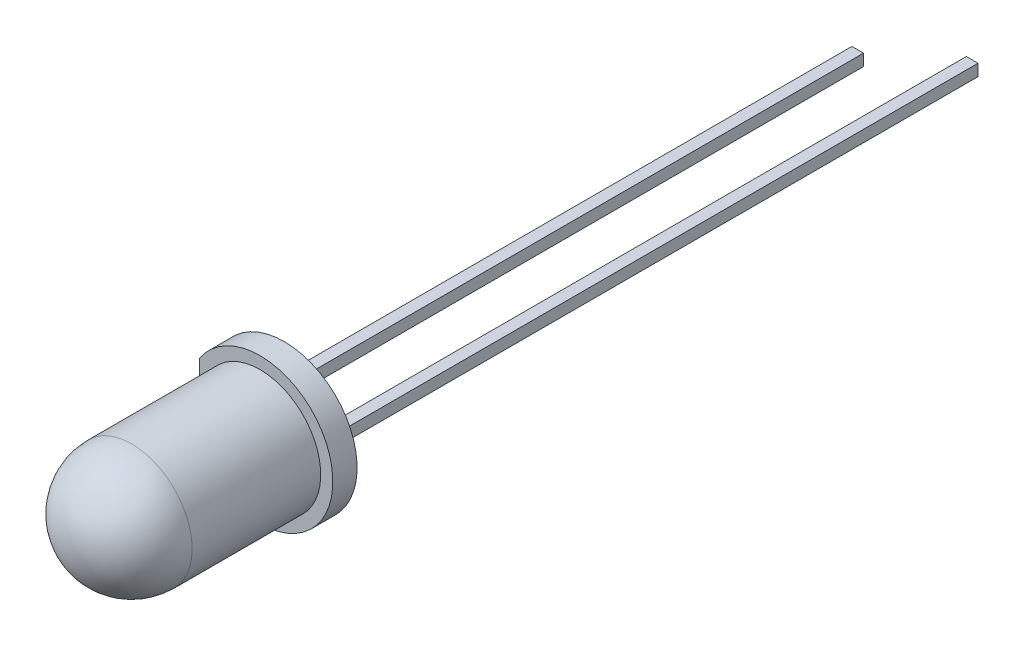
SolidWorks part; units mm, degrees
ref_plane "Plano frontal" through (0, 0, 0) normal (0, 0, 1) x (1, 0, 0)
ref_plane "Plano superior" through (0, 0, 0) normal (0, 1, 0) x (1, 0, 0)
ref_plane "Plano direito" through (0, 0, 0) normal (1, 0, 0) x (0, 0, -1)
sketch "Esboço1" plane through (0, 0, 0) normal (0, 0, 1) x (1, 0, 0)
  circle A0 centre (0, 0) radius 3
extrude "Ressalto-extrusão1" add sketch "Esboço1" along normal blind 1
sketch "Esboço3" plane through (0, 0, 0) normal (1, 0, 0) x (0, 0, -1)
  line L0 (-1, 0) -> (-8.8, 0)
  line L1 (-1, 3) -> (-1, -3) construction
  line L2 (-6.3, 2.5) -> (-1, 2.5)
  line L3 (-1, 0) -> (-1, 2.5)
  arc A0 (-8.8, 0) -> (-6.3, 2.5) centre (-6.3, 0) cw
revolve "Revolução1" add sketch "Esboço3" angle 360 about L0
sketch "Esboço4" plane through (0, 0, 0) normal (0, 0, -1) x (-1, 0, 0)
  line L0 (2.5, 1.6583) -> (2.5, -1.6583)
  circle A0 centre (0, 0) radius 3 construction
  arc A1 (2.5, -1.6583) -> (2.5, 1.6583) centre (0, 0) ccw
  circle A2 centre (0, 0) radius 2.5 construction
extrude "Corte-extrusão1" cut sketch "Esboço4" against normal up to surface (1 mm away) up to face at (2.5, 0, 1)
sketch "Esboço5" plane through (0, 0, 0) normal (0, 0, -1) x (-1, 0, 0)
  line L0 (-1.12, 0) -> (1.12, 0) construction
  line L1 (-1.6, -0.24) -> (-1.12, -0.24)
  line L2 (-1.6, -0.24) -> (-1.6, 0.24)
  line L3 (-1.6, 0.24) -> (-1.12, 0.24)
  line L4 (-1.12, -0.24) -> (-1.12, 0.24)
  line L5 (1.12, -0.24) -> (1.6, -0.24)
  line L6 (1.12, -0.24) -> (1.12, 0.24)
  line L7 (1.12, 0.24) -> (1.6, 0.24)
  line L8 (1.6, -0.24) -> (1.6, 0.24)
extrude "Ressalto-extrusão2" add sketch "Esboço5" along normal blind 25 separate body
sketch "Esboço6" plane through (0, 0, -25) normal (0, 0, -1) x (-1, 0, 0)
  line L4 (-1.6, 0.24) -> (-1.6, -0.24)
  line L5 (-1.6, -0.24) -> (-1.12, -0.24)
  line L6 (-1.12, -0.24) -> (-1.12, 0.24)
  line L7 (-1.12, 0.24) -> (-1.6, 0.24)
  line L8 (-1.6, 0.24) -> (-1.6, -0.24)
  line L9 (-1.6, -0.24) -> (-1.12, -0.24)
  line L10 (-1.12, -0.24) -> (-1.12, 0.24)
  line L11 (-1.12, 0.24) -> (-1.6, 0.24)
extrude "Ressalto-extrusão3" add sketch "Esboço6" along normal blind 2 separate body
sketch "Esboço7" plane through (0, 0, 0) normal (0, 1, 0) x (1, 0, 0)
  line L0 (-1.6, 0) -> (-1.6, -3.5)
  line L1 (-1.12, 0) -> (-1.12, -2)
  line L2 (0.02, -2) -> (1.2, -4)
  line L3 (1.2, -4) -> (-1.3, -4)
  line L4 (-1.3, -4) -> (-1.6, -3.5)
  line L5 (-1.12, -2) -> (0.02, -2)
  line L6 (1.6, 0) -> (1.6, -4)
  line L7 (1.6, -4) -> (1.4, -4)
  line L8 (1.4, -4) -> (0.22, -2)
  line L9 (0.22, -2) -> (1.12, -2)
  line L10 (1.12, -2) -> (1.12, 0)
  line L11 (-1.6, 0) -> (-1.12, 0)
  line L12 (1.12, 0) -> (1.6, 0)
extrude "Corte-extrusão2" cut sketch "Esboço7" against normal mid plane 0.48
sketch "Esboço8" plane through (0, 0, 0) normal (0, 1, 0) x (1, 0, 0)
  line L0 (-1.3, -4) -> (1.2, -4) construction
  line L1 (-1.6, -3.5) -> (-1.3, -4) construction
  line L2 (-1.6, 0) -> (-1.6, -3.5) construction
  line L3 (1.2, -4) -> (0.02, -2) construction
  line L4 (0.02, -2) -> (-1.12, -2) construction
  line L5 (-1.12, -2) -> (-1.12, 0) construction
  line L6 (0.22, -2) -> (1.4, -4) construction
  line L7 (1.12, -2) -> (0.22, -2) construction
  line L8 (1.12, 0) -> (1.12, -2) construction
  line L9 (1.6, -4) -> (1.6, 0) construction
  line L10 (1.4, -4) -> (1.6, -4) construction
  line L11 (-1.12, 0) -> (-1.6, 0) construction
  line L12 (1.6, 0) -> (1.12, 0) construction
  line L13 (-1.3, -4) -> (1.2, -4)
  line L14 (-1.6, -3.5) -> (-1.3, -4)
  line L15 (-1.6, 0) -> (-1.6, -3.5)
  line L16 (1.2, -4) -> (0.02, -2)
  line L17 (0.02, -2) -> (-1.12, -2)
  line L18 (-1.12, -2) -> (-1.12, 0)
  line L19 (0.22, -2) -> (1.4, -4)
  line L20 (1.12, -2) -> (0.22, -2)
  line L21 (1.12, 0) -> (1.12, -2)
  line L22 (1.6, -4) -> (1.6, 0)
  line L23 (1.4, -4) -> (1.6, -4)
  line L24 (-1.12, 0) -> (-1.6, 0)
  line L25 (1.6, 0) -> (1.12, 0)
extrude "Ressalto-extrusão4" add sketch "Esboço8" along normal mid plane 0.48 separate body
combine bodies "Combinar1" operation type add bodies to combine 109 106 104
combine bodies "Combinar2" operation type add bodies to combine 108 105
sketch "Esboço10" plane through (0, 0, 0) normal (0, 1, 0) x (1, 0, 0)
  line L0 (-0.05, -4) -> (-0.05, -3.7)
  line L1 (-1.3, -4) -> (1.2, -4) construction
  line L2 (-0.55, -4) -> (-0.05, -4)
  arc A0 (-0.05, -3.7) -> (-0.55, -4) centre (-0.05, -4.2667) ccw
revolve "Corte-Revolução1" cut sketch "Esboço10" angle 360 about L0
sketch "Esboço11" plane through (0, 0, 0) normal (0, 1, 0) x (1, 0, 0)
  line L0 (-0.55, -4) -> (-0.05, -4) construction
  line L1 (-0.05, -4) -> (-0.05, -3.7) construction
  line L2 (-0.55, -4) -> (-0.05, -4)
  line L3 (-0.05, -4) -> (-0.05, -3.7)
  arc A0 (-0.05, -3.7) -> (-0.55, -4) centre (-0.05, -4.2667) ccw construction
  arc A1 (-0.05, -3.7) -> (-0.55, -4) centre (-0.05, -4.2667) ccw
revolve "Revolução2" add sketch "Esboço11" angle 360 about L3
combine bodies "Combinar3" operation type add bodies to combine 113 112
sketch "Esboço12" plane through (0, 0, 4) normal (0, 0, 1) x (1, 0, 0)
  circle A0 centre (-0.05, 0) radius 0.2
  arc A1 (0.3886, 0.24) -> (-0.4886, 0.24) centre (-0.05, 0) ccw construction
extrude "Corte-extrusão3" cut sketch "Esboço12" against normal blind 0.1
sketch "Esboço13" plane through (0, 0, 0) normal (0, 1, 0) x (1, 0, 0)
  line L0 (1.6, 27) -> (-7.0603, 32)
  line L1 (1.6, 27) -> (1.12, 27) construction
ref_plane "Plano1" through (12.0913, 0, -20.9428) normal (0.5, 0, -0.866) x (-0.866, 0, -0.5)
